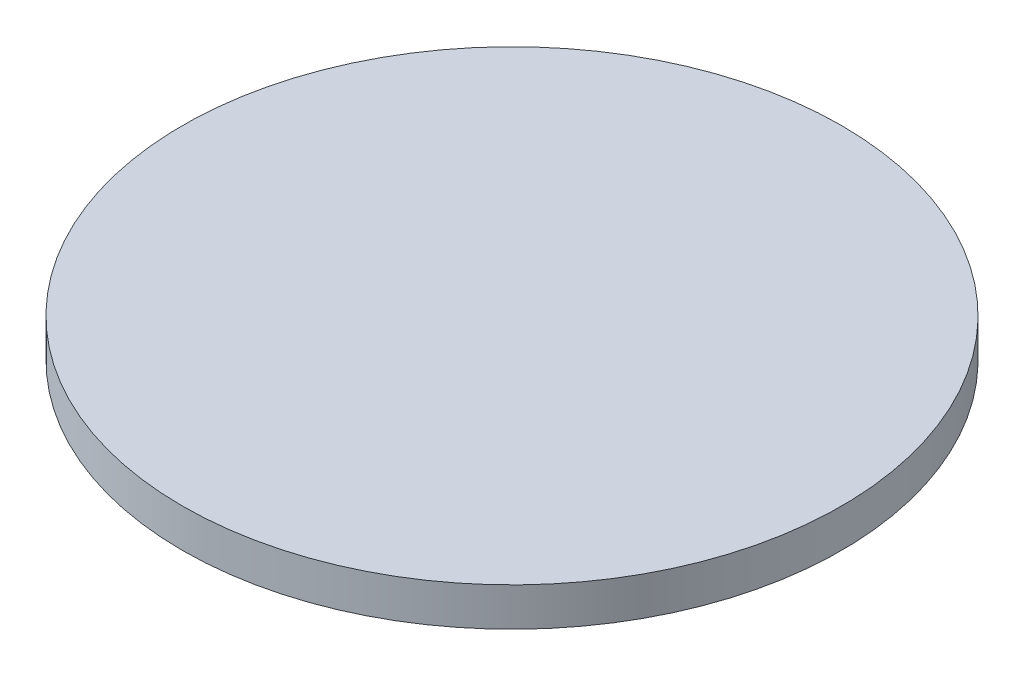
SolidWorks part; units mm, degrees
ref_plane "Front" through (0, 0, 0) normal (0, 0, 1) x (1, 0, 0)
ref_plane "Top" through (0, 0, 0) normal (0, 1, 0) x (1, 0, 0)
ref_plane "Right" through (0, 0, 0) normal (1, 0, 0) x (0, 0, -1)
sketch "Sketch1" plane through (0, 0, 0) normal (0, 1, 0) x (1, 0, 0)
  circle A0 centre (0, 0) radius 60
  dimension "D1" = 120
extrude "Boss-Extrude1" add sketch "Sketch1" along normal blind 7
sketch "Sketch2" plane through (0, 7, 0) normal (0, 1, 0) x (1, 0, 0)
  circle A0 centre (0, 0) radius 37.5
  circle A1 centre (0, 0) radius 32.5
  dimension "D1" = 75
  dimension "D2" = 5
